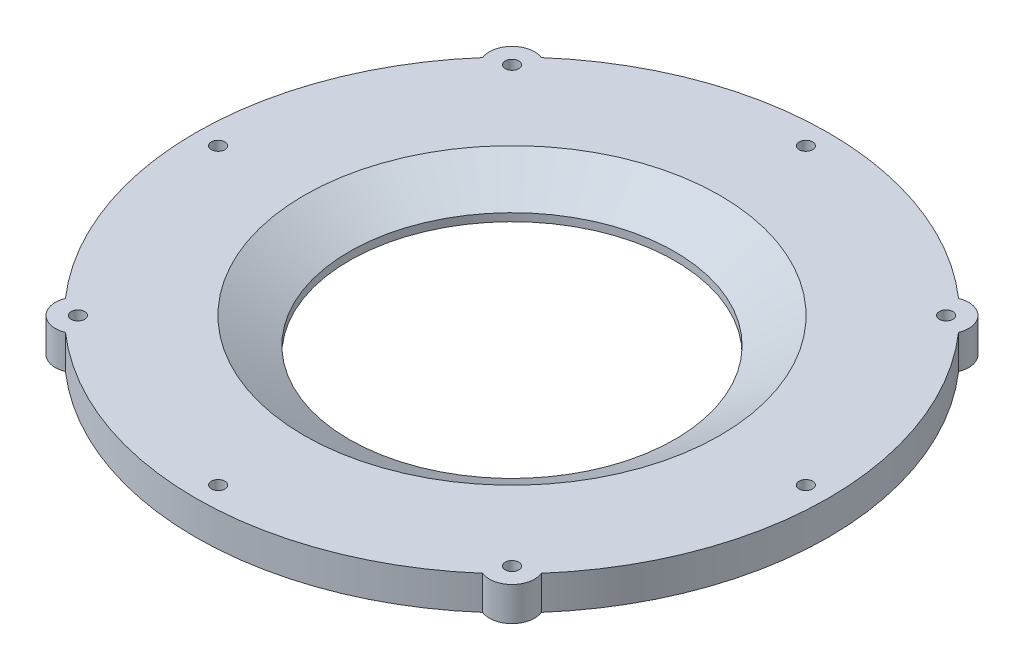
SolidWorks part; units mm, degrees
material "6061-T6 (SS)"
ref_plane "Front Plane" through (0, 0, 0) normal (0, 0, 1) x (1, 0, 0)
ref_plane "Top Plane" through (0, 0, 0) normal (0, 1, 0) x (1, 0, 0)
ref_plane "Right Plane" through (0, 0, 0) normal (1, 0, 0) x (0, 0, -1)
sketch "Sketch1" plane through (0, 0, 0) normal (0, 1, 0) x (1, 0, 0)
  line L0 (0, 88.9) -> (0, -88.9) construction
  line L1 (-88.9, 0) -> (88.9, 0) construction
  line L2 (-60.9759, -60.9759) -> (60.9759, 60.9759) construction
  line L3 (60.9759, -60.9759) -> (-60.9759, 60.9759) construction
  arc A0 (-66.8608, 58.5904) -> (-66.8608, -58.5904) centre (0, 0) ccw
  arc A1 (-58.5904, 66.8608) -> (-66.8608, 58.5904) centre (-60.9759, 60.9759) ccw
  arc A2 (66.8608, 58.5904) -> (58.5904, 66.8608) centre (60.9759, 60.9759) ccw
  arc A3 (58.5904, -66.8608) -> (66.8608, -58.5904) centre (60.9759, -60.9759) ccw
  arc A4 (-66.8608, -58.5904) -> (-58.5904, -66.8608) centre (-60.9759, -60.9759) ccw
  arc A5 (58.5904, 66.8608) -> (-58.5904, 66.8608) centre (0, 0) ccw
  arc A6 (66.8608, -58.5904) -> (66.8608, 58.5904) centre (0, 0) ccw
  arc A7 (-58.5904, -66.8608) -> (58.5904, -66.8608) centre (0, 0) ccw
  circle A8 centre (-60.9759, 60.9759) radius 1.905
  circle A9 centre (60.9759, 60.9759) radius 1.905
  circle A10 centre (60.9759, -60.9759) radius 1.905
  circle A11 centre (-60.9759, -60.9759) radius 1.905
  circle A12 centre (0, 0) radius 83.82 construction
  point P10 (0, 0)
  point P13 (0, 0)
  dimension "D1" = 177.8
  dimension "D3" = 12.7
  dimension "D4" = 3.81
  dimension "D7" = 167.64
  dimension "D2" = 90
  dimension "D5" = 45
  dimension "D6" = 172.466
extrude "Boss-Extrude1" add sketch "Sketch1" along normal blind 9.525
sketch "Sketch2" plane through (0, 9.525, 0) normal (0, 1, 0) x (1, 0, 0)
  circle A0 centre (0, 0) radius 45.72
extrude "Cut-Extrude1" cut sketch "Sketch2" against normal blind 12.7
sketch "Sketch4" plane through (0, 9.525, 0) normal (0, 1, 0) x (1, 0, 0)
  line L0 (0, 0) -> (0, 115.2639) construction
  circle A0 centre (0, 82.55) radius 1.905
  dimension "D1" = 3.81
  dimension "D2" = 82.55
extrude "Cut-Extrude3" cut sketch "Sketch4" against normal blind 12.7
pattern_circular "CirPattern2" count 4 over 360 about axis through (0, 0, 0) along (0, 1, 0) of "Cut-Extrude3"
ref_plane "Plane3" through (-62.8618, 0, -62.8618) normal (-0.7071, 0, -0.7071) x (0, -1, 0)
sketch "Sketch10" plane through (-62.8618, 0, -62.8618) normal (-0.7071, 0, -0.7071) x (0, -1, 0)
  line L0 (0, 0) -> (-9.652, 0) construction
  circle A1 centre (-4.826, 0) radius 0.6985
  dimension "D2" = 1.397
  dimension "D1" = 9.652
extrude "Cut-Extrude5" cut sketch "Sketch10" against normal blind 3.175
pattern_circular "CirPattern5" count 4 over 360 about axis through (0, 0, 0) along (0, 1, 0) of "Cut-Extrude5"
chamfer "Chamfer1" distance 12.7 angle 30 1 edges at (0, 9.525, 45.72)
